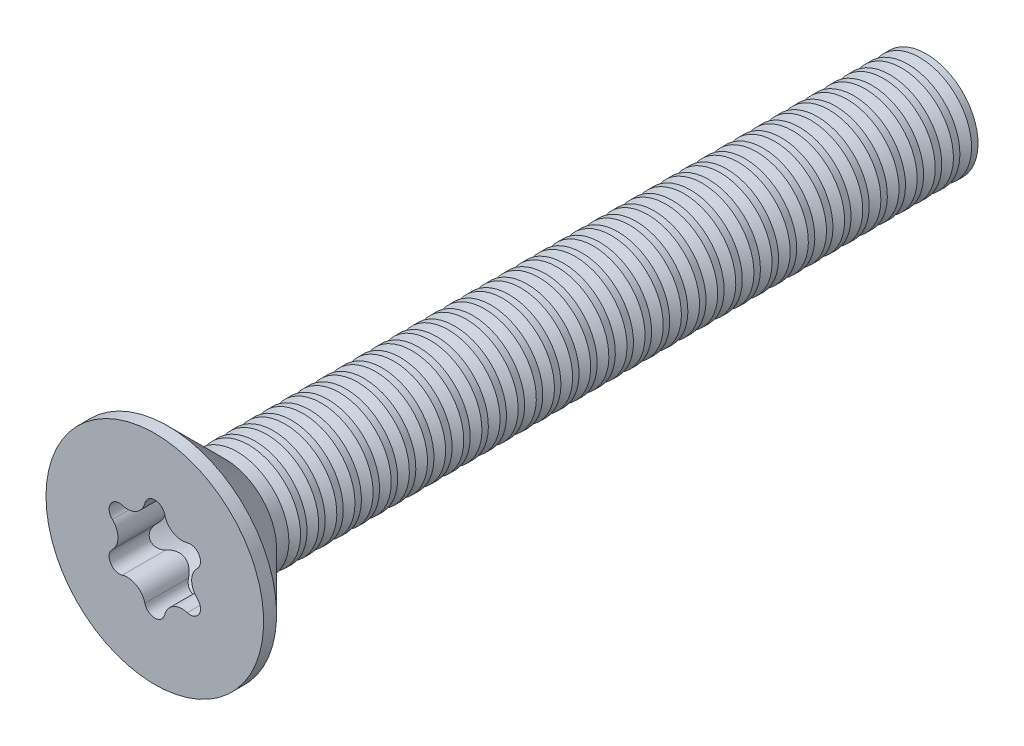
SolidWorks part; units mm, degrees
ref_plane "Front Plane" through (0, 0, 0) normal (0, 0, 1) x (1, 0, 0)
ref_plane "Top Plane" through (0, 0, 0) normal (0, 1, 0) x (1, 0, 0)
ref_plane "Right Plane" through (0, 0, 0) normal (1, 0, 0) x (0, 0, -1)
sketch "BodySke" plane through (0, 0, 0) normal (1, 0, 0) x (0, 0, -1)
  line L0 (0, 0) -> (-1787.2758, 0) construction
  line L1 (0, 0) -> (0, 4.2)
  line L2 (0.5, 4.2) -> (2.7, 2)
  line L3 (0.5, -4.2) -> (2.7, -2) construction
  line L4 (2.7, 2) -> (30, 2)
  line L5 (30, 2) -> (30, 0)
  line L6 (30, 0) -> (0, 0)
  line L7 (0, 0) -> (0, 50000) construction
  line L8 (0.5, 4.2) -> (0, 4.2)
  dimension "D" = 4
  dimension "Dk" = 8.4
  dimension "K" = 2.7
  dimension "L" = 30
  dimension "D1" = 90
  dimension "B" = 30
revolve "Base-Revolve" add sketch "BodySke" angle 360 about L0
cosmetic thread "ThreadCosmetic" [suppressed] parameters "ThdLen"=27.3, "MinorDia"=3.22
sketch "PreBSke" plane through (0, 0, 0) normal (1, 0, 0) x (0, 0, -1)
  line L0 (0, 0) -> (-50000, 0) construction
  line L1 (0, 0) -> (0, 1.975)
  line L2 (0, 4.7) -> (0, -4.7) construction
  line L3 (0, 1.975) -> (1.53, 1.975)
  line L4 (1.53, 1.975) -> (2.7167, 0)
  line L5 (2.7167, 0) -> (0, 0)
  line L6 (1.53, -1.975) -> (2.7167, 0) construction
  dimension "T" = 1.53
  dimension "A" = 3.95
  dimension "D1" = 118
revolve "PreBroach" cut sketch "PreBSke" angle 360 about L0
sketch "HexSke" plane through (0, 0, 0) normal (0, 0, 1) x (1, 0, 0)
  line L0 (0, 0) -> (-43301.2702, 25000) construction
  line L1 (0, 0) -> (-43301.2702, -25000) construction
  line L2 (0, 0) -> (50000, 0) construction
  arc A0 (-1.6394, -0.5027) -> (-1.6394, 0.5027) centre (-2.1139, 0) ccw
  arc A1 (-1.7104, 0.9875) -> (-1.6394, 0.5027) centre (-1.3683, 0.79) ccw
  arc A2 (-1.6394, -0.5027) -> (-1.7104, -0.9875) centre (-1.3683, -0.79) ccw
  arc A3 (-1.2551, 1.1684) -> (-1.7104, 0.9875) centre (-1.3683, 0.79) ccw
  circle A4 centre (0, 0) radius 1.4226 construction
  circle A5 centre (0, 0) radius 1.975 construction
  arc A6 (-1.2551, 1.1684) -> (-0.3843, 1.6711) centre (-1.0569, 1.8307) ccw
  arc A7 (0, 1.975) -> (-0.3843, 1.6711) centre (0, 1.58) ccw
  arc A8 (0.3843, 1.6711) -> (0, 1.975) centre (0, 1.58) ccw
  arc A9 (0.3843, 1.6711) -> (1.2551, 1.1684) centre (1.0569, 1.8307) ccw
  arc A10 (1.7104, 0.9875) -> (1.2551, 1.1684) centre (1.3683, 0.79) ccw
  arc A11 (1.6394, 0.5027) -> (1.7104, 0.9875) centre (1.3683, 0.79) ccw
  arc A12 (1.6394, 0.5027) -> (1.6394, -0.5027) centre (2.1139, 0) ccw
  arc A13 (1.7104, -0.9875) -> (1.6394, -0.5027) centre (1.3683, -0.79) ccw
  arc A14 (1.2551, -1.1684) -> (1.7104, -0.9875) centre (1.3683, -0.79) ccw
  arc A15 (1.2551, -1.1684) -> (0.3843, -1.6711) centre (1.0569, -1.8307) ccw
  arc A16 (0, -1.975) -> (0.3843, -1.6711) centre (0, -1.58) ccw
  arc A17 (-0.3843, -1.6711) -> (0, -1.975) centre (0, -1.58) ccw
  arc A18 (-0.3843, -1.6711) -> (-1.2551, -1.1684) centre (-1.0569, -1.8307) ccw
  arc A19 (-1.7104, -0.9875) -> (-1.2551, -1.1684) centre (-1.3683, -0.79) ccw
  circle A20 centre (0, 0) radius 1.975 construction
  circle A21 centre (0, 0) radius 1.975
  point P56 (0, 0)
  circle M6 centre (0, 0) radius 1.975
  dimension "B" = 2.8452
  dimension "Ri" = 0.395
  dimension "Re" = 0.6913
  dimension "D1" = 60
  dimension "D5" = 6
extrude "Hexalobular" add sketch "HexSke" against normal up to next contours A2 A0 A1 M6 | A7 A3 A6 M6 | A10 A8 A9 M6 | A13 A11 A12 M6 | A16 A14 A15 M6 | A19 A17 A18 M6
sketch "ThdSchSke" plane through (0, 0, 0) normal (1, 0, 0) x (0, 0, -1)
  line L0 (30.2252, 2) -> (30, 1.61)
  line L1 (30, 1.61) -> (29.7748, 2)
  line L2 (29.7748, 2) -> (30.2252, 2)
  line L3 (30, 1.61) -> (30, 2) construction
  line L4 (30, -2) -> (30, 2) construction
  line L5 (30, 2) -> (2.7, 2) construction
  line L6 (0, 0) -> (-50000, 0) construction
  dimension "MinorDia" = 3.22
  dimension "D1" = 60
  dimension "D2" = 0.4503
revolve "ThreadSchematic" cut sketch "ThdSchSke" angle 360 about L6
ref_plane "ThreadPlane" through (0, 0, -2.7) normal (0, 0, -1) x (-1, 0, 0)
pattern_linear "ThdSchPat" count 39 spacing 0.7 along (0, 0, 1) of "ThreadSchematic"
equation "\"MinorDia@ThreadCosmetic\" = \"MinorDia@ThdSchSke\""
equation "\"ThdLen@ThreadCosmetic\" = \"ThreadLength\""
equation "\"Ri@HexSke\"= .1 * \"A@PreBSke\""
equation "\"Re@HexSke\"= .175 * \"A@PreBSke\""
equation "\"ThreadLength\"= IIF ( \"B@BodySke\" = \"L@BodySke\" , \"L@BodySke\" - \"K@BodySke\" , \"B@BodySke\" )"
equation "\"ThdLen@ThreadPlane\"=\"ThreadLength\""
